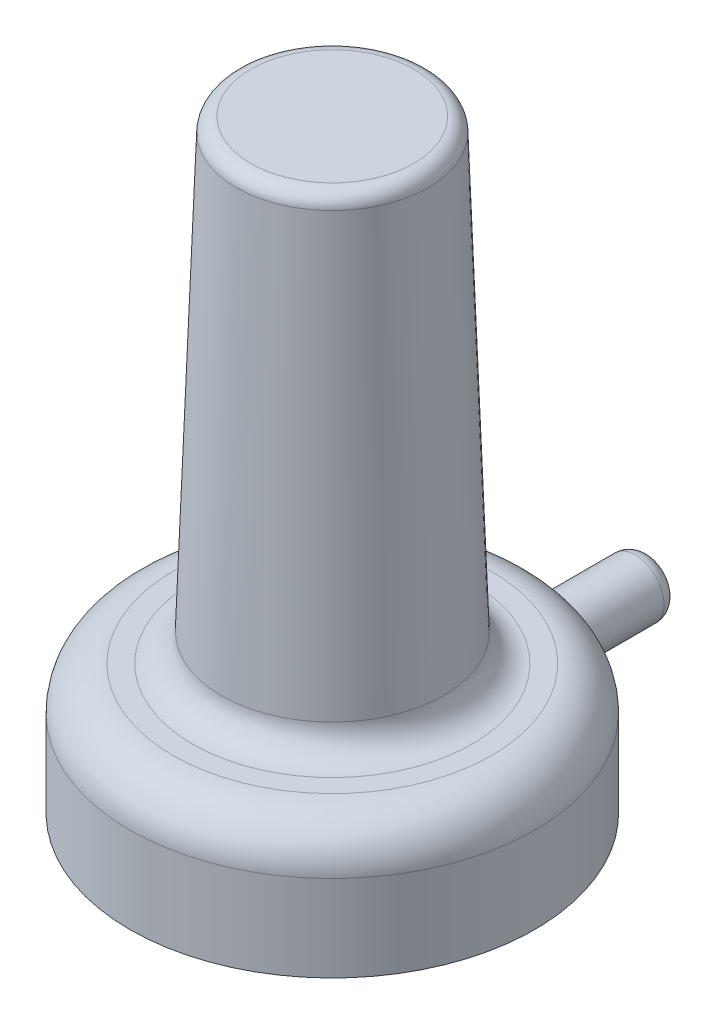
SolidWorks part; units mm, degrees
ref_plane "Front Plane" through (0, 0, 0) normal (0, 0, 1) x (1, 0, 0)
ref_plane "Top Plane" through (0, 0, 0) normal (0, 1, 0) x (1, 0, 0)
ref_plane "Right Plane" through (0, 0, 0) normal (1, 0, 0) x (0, 0, -1)
sketch "Sketch1" plane through (0, 0, 0) normal (0, 1, 0) x (1, 0, 0)
  circle A0 centre (0, 0) radius 17.907
  dimension "D1" = 35.814
extrude "Boss-Extrude1" add sketch "Sketch1" along normal blind 53.34
ref_plane "Plane1" through (0, 11.43, 0) normal (0, 1, 0) x (1, 0, 0)
sketch "Sketch2" plane through (0, 11.43, 0) normal (0, 1, 0) x (1, 0, 0)
  circle A0 centre (0, 0) radius 9.906
  dimension "D1" = 19.812
extrude "Cut-Extrude1" cut sketch "Sketch2" along normal up to surface (41.91 mm away) draft 2 flip side to cut
fillet "Fillet1" radius 1.27 1 edges at (0, 53.34, 8.4425)
fillet "Fillet2" radius 3.81 1 edges at (0, 11.43, 17.907)
fillet "Fillet3" radius 2.54 1 edges at (0, 11.43, 9.906)
sketch "Sketch4" plane through (0, 0, 0) normal (0, 0, 1) x (1, 0, 0)
  line L0 (0, 54.5409) -> (0, 36.5401) construction
  line L1 (-17.907, 0) -> (17.907, 0) construction
  circle A0 centre (0, 3.81) radius 2.54
  dimension "D1" = 5.08
  dimension "D2" = 3.81
extrude "Boss-Extrude3" add sketch "Sketch4" against normal blind 28.067
fillet "Fillet4" radius 1.27 1 edges at (2.54, 3.81, -28.067)
